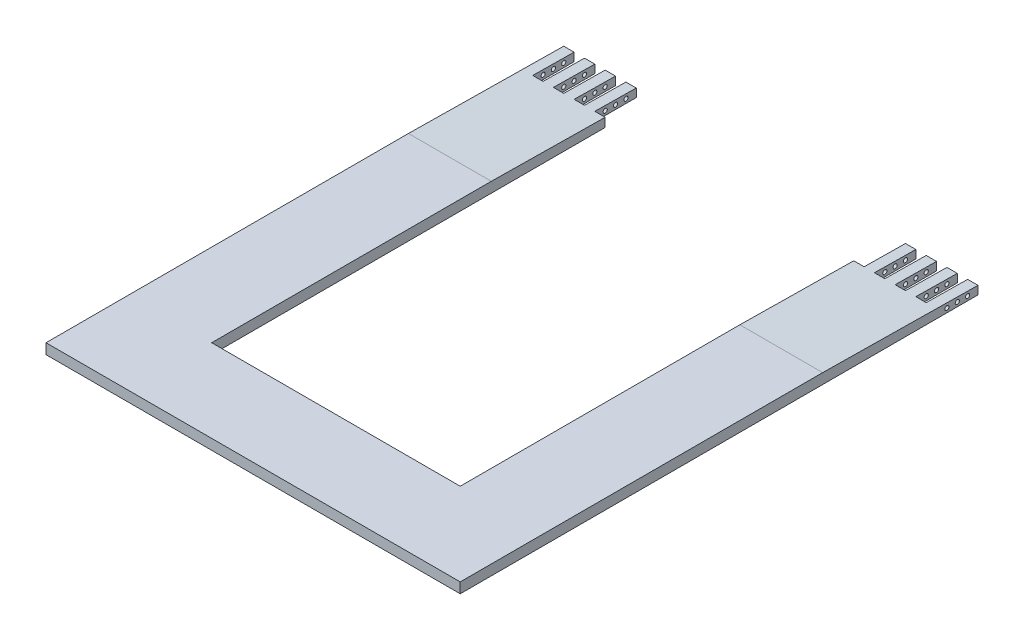
SolidWorks part; units mm, degrees
ref_plane "前视基准面" through (0, 0, 0) normal (0, 0, 1) x (1, 0, 0)
ref_plane "上视基准面" through (0, 0, 0) normal (0, 1, 0) x (1, 0, 0)
ref_plane "右视基准面" through (0, 0, 0) normal (1, 0, 0) x (0, 0, -1)
sketch "草图1" plane through (0, 0, 0) normal (0, 1, 0) x (1, 0, 0)
  line L1 (-100, -20) -> (100, -20)
  line L2 (-100, -20) -> (-100, 20)
  line L3 (-100, 20) -> (100, 20)
  line L4 (100, -20) -> (100, 20)
  line L5 (-100, -20) -> (100, 20) construction
  line L6 (-100, 20) -> (100, -20) construction
  line L7 (100, -20) -> (60, -20)
  line L8 (100, -20) -> (100, 455)
  line L9 (100, 455) -> (60, 455)
  line L10 (60, -20) -> (60, 455)
  line L11 (-100, -20) -> (-60, -20)
  line L12 (-100, -20) -> (-100, 455)
  line L13 (-100, 455) -> (-60, 455)
  line L14 (-60, -20) -> (-60, 455)
  point P0 (0, 0)
  dimension "D1" = 200
  dimension "D2" = 40
  dimension "D3" = 475
  dimension "D4" = 475
  dimension "D5" = 40
  dimension "D6" = 40
extrude "凸台-拉伸1" add sketch "草图1" along normal blind 5 contours L3 L14 L13 L12 | L1 L14 L3 L2 | L14 L1 L10 L3 | L10 L1 L4 L3 | L10 L3 L8 L9
sketch "草图2" plane through (100, 0, 0) normal (1, 0, 0) x (0, 0, -1)
  line L0 (455, 0) -> (455, 5)
  line L1 (455, 5) -> (155, 5)
  line L2 (-20, 5) -> (455, 5) construction
  line L3 (155, 5) -> (455, 1)
  line M4 (455, 5) -> (-20, 5)
  dimension "D1" = 1
  dimension "D2" = 300
extrude "切除-拉伸2" cut sketch "草图2" against normal through all contours L3 L0 M4
sketch "草图3" plane through (0, 5, 0) normal (0, 1, 0) x (1, 0, 0)
  line L0 (100, 155) -> (100, 455) construction
  line L1 (-100, -20) -> (100, -20)
  line L2 (-100, -20) -> (-100, 230)
  line L3 (-100, 230) -> (100, 230)
  line L4 (100, -20) -> (100, 230)
  line L5 (-100, 230) -> (-95, 230)
  line L6 (-95, 230) -> (-95, 210)
  line L7 (-95, 210) -> (-90, 210)
  line L8 (-90, 210) -> (-90, 230)
  line L9 (-90, 230) -> (-85, 230)
  line L10 (-85, 230) -> (-85, 210)
  line L11 (-85, 210) -> (-80, 210)
  line L12 (-60, 455) -> (-60, 155) construction
  line L13 (-60, 210) -> (-60, 230)
  line L14 (100, 230) -> (75, 230)
  line L15 (75, 230) -> (75, 210)
  line L16 (75, 210) -> (70, 210)
  line L17 (70, 210) -> (70, 230)
  line L18 (70, 230) -> (65, 230)
  line L19 (65, 230) -> (65, 210)
  line L20 (65, 210) -> (60, 210)
  line L21 (60, 455) -> (60, 155) construction
  line L22 (60, 210) -> (60, 230)
  line L23 (-100, 230) -> (-100, 455)
  line L24 (-100, 455) -> (100, 455)
  line L25 (100, 455) -> (100, 230)
  line L26 (-80, 210) -> (-80, 230)
  line L27 (-80, 230) -> (-75, 230)
  line L28 (-75, 230) -> (-75, 210)
  line L29 (-75, 210) -> (-70, 210)
  line L30 (-70, 210) -> (-70, 230)
  line L31 (-70, 230) -> (-65, 230)
  line L32 (-65, 230) -> (-65, 210)
  line L33 (-65, 210) -> (-60, 210)
  line L34 (75, 230) -> (80, 230)
  line L35 (80, 230) -> (80, 210)
  line L36 (80, 210) -> (85, 210)
  line L37 (85, 210) -> (85, 230)
  line L38 (85, 230) -> (90, 230)
  line L39 (90, 230) -> (90, 210)
  line L40 (90, 210) -> (95, 210)
  line L41 (95, 210) -> (95, 230)
  dimension "D1" = 250
  dimension "D2" = 5
  dimension "D3" = 5
  dimension "D4" = 5
  dimension "D5" = 5
  dimension "D6" = 5
  dimension "D7" = 5
  dimension "D8" = 20
  dimension "D9" = 20
  dimension "D10" = 5
  dimension "D11" = 5
  dimension "D12" = 5
  dimension "D13" = 5
  dimension "D14" = 5
  dimension "D15" = 5
  dimension "D16" = 5
  dimension "D17" = 5
extrude "切除-拉伸3" cut sketch "草图3" against normal through all contours L25 L24 L23 L3 L14 | L7 L8 L3 L6 | L11 L26 L3 L10 | L29 L30 L3 L28 | L32 L33 L13 L3 | L22 L20 L19 L3 | L17 L16 L15 L3 | L36 L37 L14 L35 | L40 L41 L14 L39
sketch "草图4" plane through (100, 0, 0) normal (1, 0, 0) x (0, 0, -1)
  line L0 (230, 0) -> (230, 4) construction
  line L1 (-20, 0) -> (230, 0) construction
  circle A0 centre (225, 2) radius 1
  circle A1 centre (220, 2) radius 1
  circle A2 centre (215, 2) radius 1
  dimension "D1" = 2
  dimension "D2" = 2
  dimension "D3" = 2
  dimension "D4" = 5
  dimension "D5" = 5
  dimension "D6" = 5
  dimension "D7" = 2
  dimension "D8" = 2
  dimension "D9" = 2
extrude "切除-拉伸4" cut sketch "草图4" against normal through all
